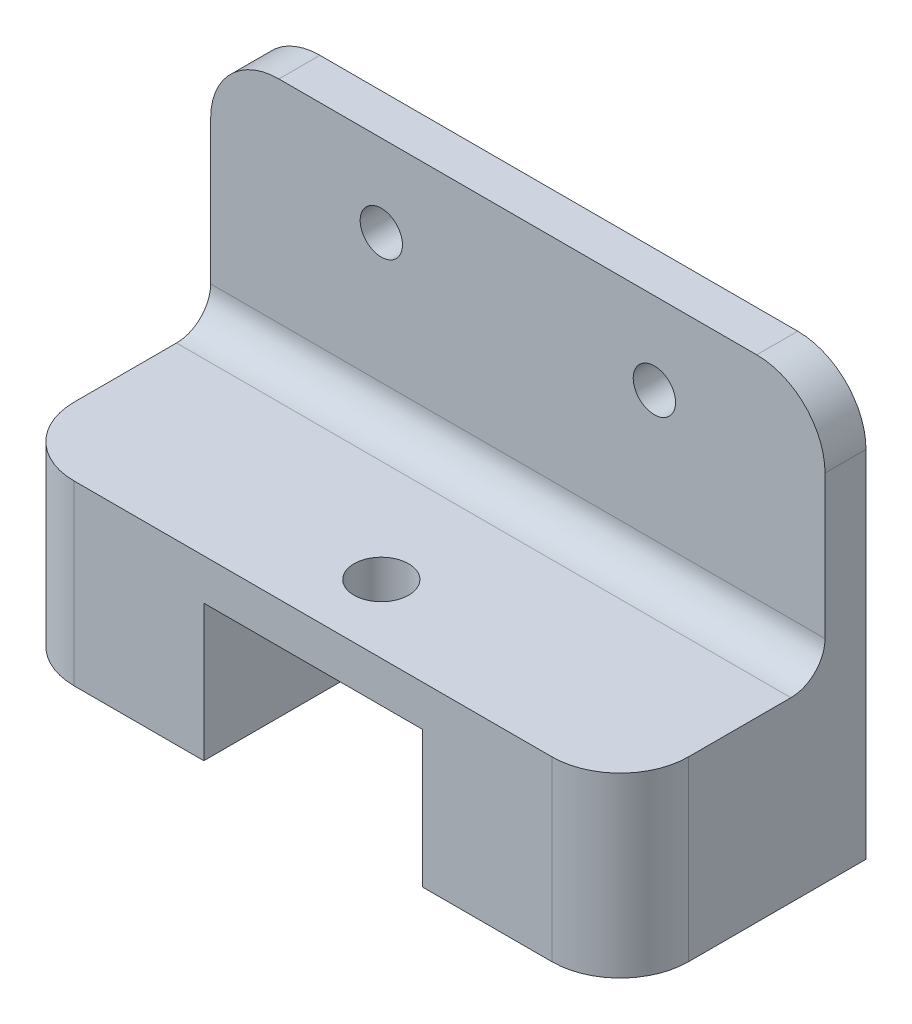
SolidWorks part; units mm, degrees
ref_plane "Alzado" through (0, 0, 0) normal (0, 0, 1) x (1, 0, 0)
ref_plane "Planta" through (0, 0, 0) normal (0, 1, 0) x (1, 0, 0)
ref_plane "Vista lateral" through (0, 0, 0) normal (1, 0, 0) x (0, 0, -1)
sketch "Croquis1" plane through (0, 0, 0) normal (1, 0, 0) x (0, 0, -1)
  line L1 (-9, -1.5) -> (9, -1.5)
  line L2 (-9, -1.5) -> (-9, 1.5)
  line L3 (-9, 1.5) -> (6, 1.5)
  line L4 (9, -1.5) -> (9, 1.5)
  line L5 (-9, -1.5) -> (9, 1.5) construction
  line L6 (-9, 1.5) -> (9, -1.5) construction
  line L8 (9, 1.5) -> (9, 19.5)
  line L9 (9, 19.5) -> (6, 19.5)
  line L10 (6, 1.5) -> (6, 19.5)
  point P0 (0, 0)
  dimension "D1" = 3
  dimension "D2" = 3
  dimension "D3" = 3
  dimension "D4" = 15
  dimension "D5" = 18
extrude "Saliente-Extruir1" add sketch "Croquis1" along normal blind 45
fillet "Redondeo1" radius 2.5 1 edges at (22.5, 1.5, -6)
sketch "Croquis2" plane through (0, 1.5, 0) normal (0, 1, 0) x (1, 0, 0)
  line L0 (45, 3.5) -> (45, -9) construction
  line L1 (45, -9) -> (0, -9) construction
  circle A0 centre (22.5, -4) radius 2
  dimension "D1" = 4
  dimension "D3" = 5
  dimension "D2" = 22.5
extrude "Cortar-Extruir1" cut sketch "Croquis2" against normal through all
sketch "Croquis3" plane through (0, 0, -9) normal (0, 0, -1) x (-1, 0, 0)
  line L0 (-22.5, 30.3406) -> (-22.5, -12.6532) construction
  line L1 (0, -1.5) -> (0, 19.5) construction
  line L2 (-45, -1.5) -> (0, -1.5) construction
  circle A0 centre (-32.5, 13.5) radius 1.55
  circle A1 centre (-12.5, 13.5) radius 1.55
  dimension "D1" = 3.1
  dimension "D3" = 15
  dimension "D4" = 10
  dimension "D2" = 22.5
extrude "Cortar-Extruir2" cut sketch "Croquis3" against normal through all
sketch "Croquis4" plane through (0, -1.5, 0) normal (0, -1, 0) x (1, 0, 0)
  line L1 (0, -9) -> (45, -9)
  line L2 (0, -9) -> (0, 9)
  line L3 (0, 9) -> (45, 9)
  line L4 (45, -9) -> (45, 9)
  dimension "D1" = 18
extrude "Saliente-Extruir2" add sketch "Croquis4" along normal blind 10
fillet "Redondeo3" radius 5 2 edges at (45, -5, 9) (0, -5, 9)
sketch "Croquis5" plane through (0, 0, 9) normal (0, 0, 1) x (1, 0, 0)
  line L0 (40, -11.5) -> (5, -11.5) construction
  line L1 (14.5, -1.5) -> (30.5, -1.5)
  line L2 (14.5, -1.5) -> (14.5, -11.5)
  line L3 (14.5, -11.5) -> (30.5, -11.5)
  line L4 (30.5, -1.5) -> (30.5, -11.5)
  line L5 (14.5, -1.5) -> (30.5, -11.5) construction
  line L6 (14.5, -11.5) -> (30.5, -1.5) construction
  line L7 (45, 1.5) -> (45, -11.5) construction
  point P0 (22.5, -6.5)
  dimension "D1" = 16
  dimension "D2" = 10
  dimension "D3" = 22.5
extrude "Cortar-Extruir3" cut sketch "Croquis5" against normal through all
fillet "Redondeo4" radius 5 2 edges at (0, 19.5, -7.5) (45, 19.5, -7.5)
